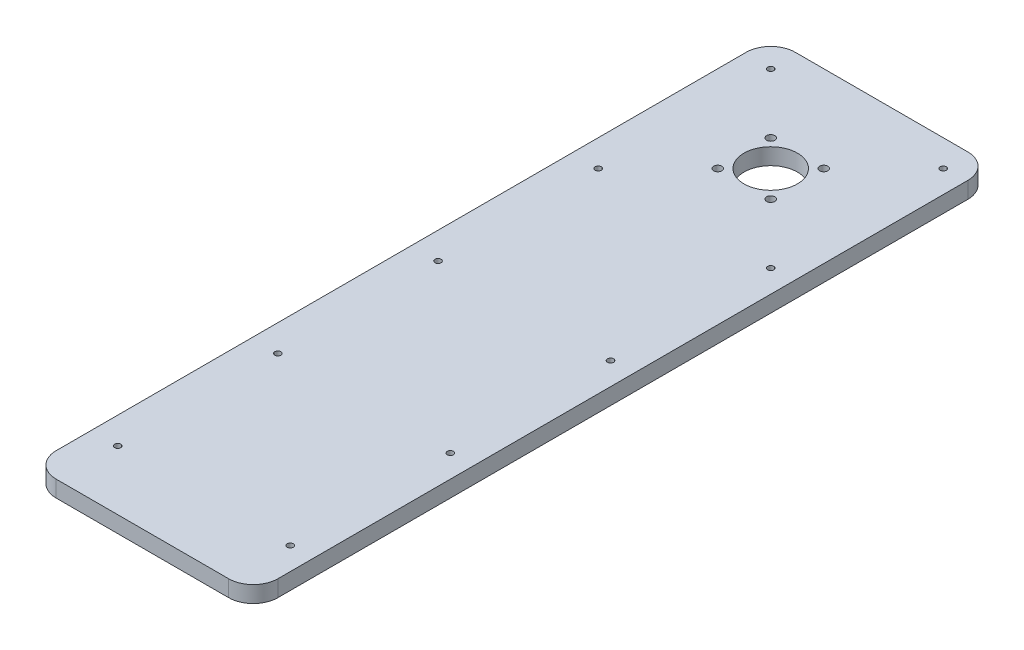
SolidWorks part; units mm, degrees
ref_plane "Front Plane" through (0, 0, 0) normal (0, 0, 1) x (1, 0, 0)
ref_plane "Top Plane" through (0, 0, 0) normal (0, 1, 0) x (1, 0, 0)
ref_plane "Right Plane" through (0, 0, 0) normal (1, 0, 0) x (0, 0, -1)
sketch "Sketch1" plane through (0, 0, 0) normal (0, 1, 0) x (1, 0, 0)
  line L0 (0, 180) -> (0, -180) construction
  line L1 (-55, -180) -> (53, -180)
  line L2 (-55, -180) -> (-55, 180)
  line L3 (-55, 180) -> (53, 180)
  line L4 (53, -180) -> (53, 180)
  line L5 (95, 240) -> (95, -240) construction
  line L7 (-42, 180) -> (-42, -180) construction
  line L11 (-12.9047, 112.0953) -> (0, 125) construction
  circle A0 centre (0, 125) radius 50 construction
  circle A1 centre (0, 125) radius 13
  circle A2 centre (-42, 83) radius 1.5
  circle A3 centre (-42, 167) radius 1.5
  circle A4 centre (42, 167) radius 1.5
  circle A5 centre (42, 83) radius 1.5
  circle A6 centre (-12.9047, 112.0953) radius 2
  circle A7 centre (-12.9047, 137.9047) radius 2
  circle A8 centre (12.9047, 137.9047) radius 2
  circle A9 centre (12.9047, 112.0953) radius 2
  circle A10 centre (-42, 5) radius 1.5
  circle A11 centre (-42, -73) radius 1.5
  circle A12 centre (-42, -151) radius 1.5
  circle A13 centre (42, -151) radius 1.5
  circle A14 centre (42, -73) radius 1.5
  circle A15 centre (42, 5) radius 1.5
  point P31 (0, 125)
  point P40 (0, 125)
  dimension "D1" = 100
  dimension "D2" = 95
  dimension "D10" = 3
  dimension "D12" = 26
  dimension "D13" = 4
  dimension "D17" = 78
  dimension "D18" = 78
  dimension "D19" = 78
  dimension "D3" = 150
  dimension "D4" = 360
  dimension "D5" = 42
  dimension "D6" = 55
  dimension "D7" = 108
  dimension "D8" = 42
  dimension "D9" = 13
  dimension "D14" = 18.25
  dimension "D16" = 45
  dimension "D11" = 4
  dimension "D15" = 4
extrude "Boss-Extrude1" add sketch "Sketch1" along normal blind 8
fillet "Fillet1" radius 12 4 edges at (53, 4, -180) (-55, 4, -180) (53, 4, 180) (-55, 4, 180)
